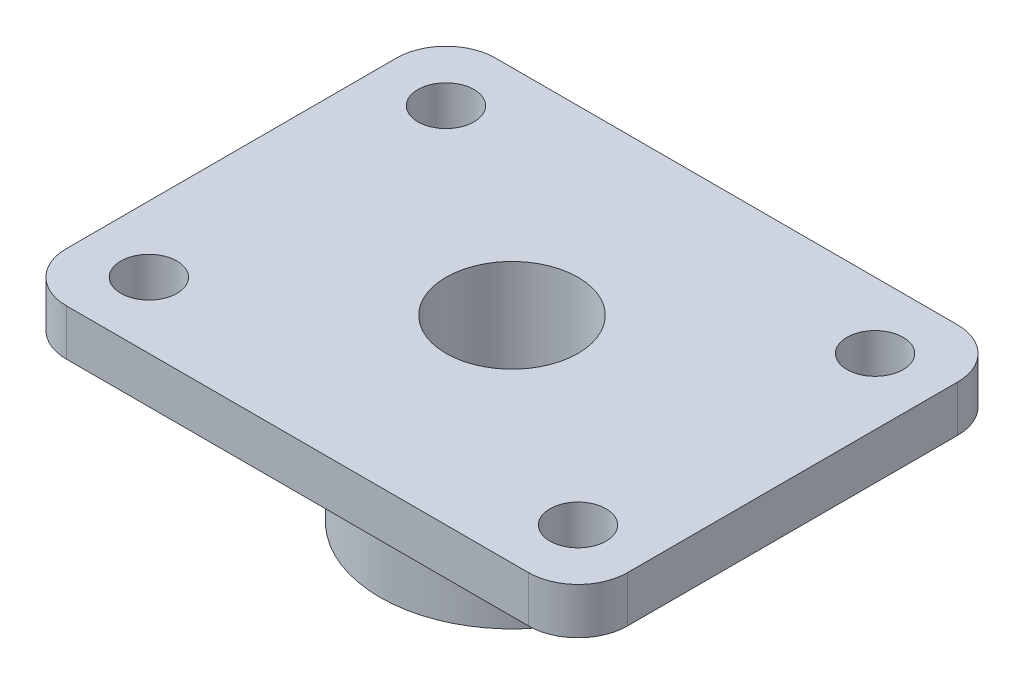
SolidWorks part; units mm, degrees
material "Acciaio al carbonio semplice"
ref_plane "Piano frontale" through (0, 0, 0) normal (0, 0, 1) x (1, 0, 0)
ref_plane "Piano superiore" through (0, 0, 0) normal (0, 1, 0) x (1, 0, 0)
ref_plane "Piano destro" through (0, 0, 0) normal (1, 0, 0) x (0, 0, -1)
sketch "Schizzo1" plane through (0, 0, 0) normal (0, 1, 0) x (1, 0, 0)
  line L0 (0, 0) -> (85, 0) construction
  line L1 (-70, 65) -> (70, 65)
  line L2 (-85, 50) -> (-85, -50)
  line L3 (-70, -65) -> (70, -65)
  line L4 (85, 50) -> (85, -50)
  line L5 (-85, 65) -> (85, -65) construction
  line L6 (-85, -65) -> (85, 65) construction
  line L7 (0, 0) -> (0, -65) construction
  circle A0 centre (0, 0) radius 20
  circle A1 centre (65, -45) radius 8.5
  arc A2 (70, -65) -> (85, -50) centre (70, -50) ccw
  circle A3 centre (65, 45) radius 8.5
  circle A4 centre (-65, -45) radius 8.5
  circle A5 centre (-65, 45) radius 8.5
  arc A6 (-85, -50) -> (-70, -65) centre (-70, -50) ccw
  arc A7 (70, 65) -> (85, 50) centre (70, 50) cw
  arc A8 (-70, 65) -> (-85, 50) centre (-70, 50) ccw
  point P0 (0, 0)
  dimension "D3" = 40
  dimension "D4" = 17
  dimension "D7" = 15
  dimension "D8" = 15
  dimension "D1" = 170
  dimension "D2" = 130
  dimension "D5" = 20
  dimension "D6" = 20
extrude "Estrusione-Estrusione1" add sketch "Schizzo1" along normal blind 14
sketch "Schizzo2" plane through (0, 0, 0) normal (0, -1, 0) x (1, 0, 0)
  circle A0 centre (0, 0) radius 40
  circle A1 centre (0, 0) radius 20 construction
  circle A2 centre (0, 0) radius 20
  dimension "D1" = 80
extrude "Estrusione-Estrusione2" add sketch "Schizzo2" along normal blind 40
